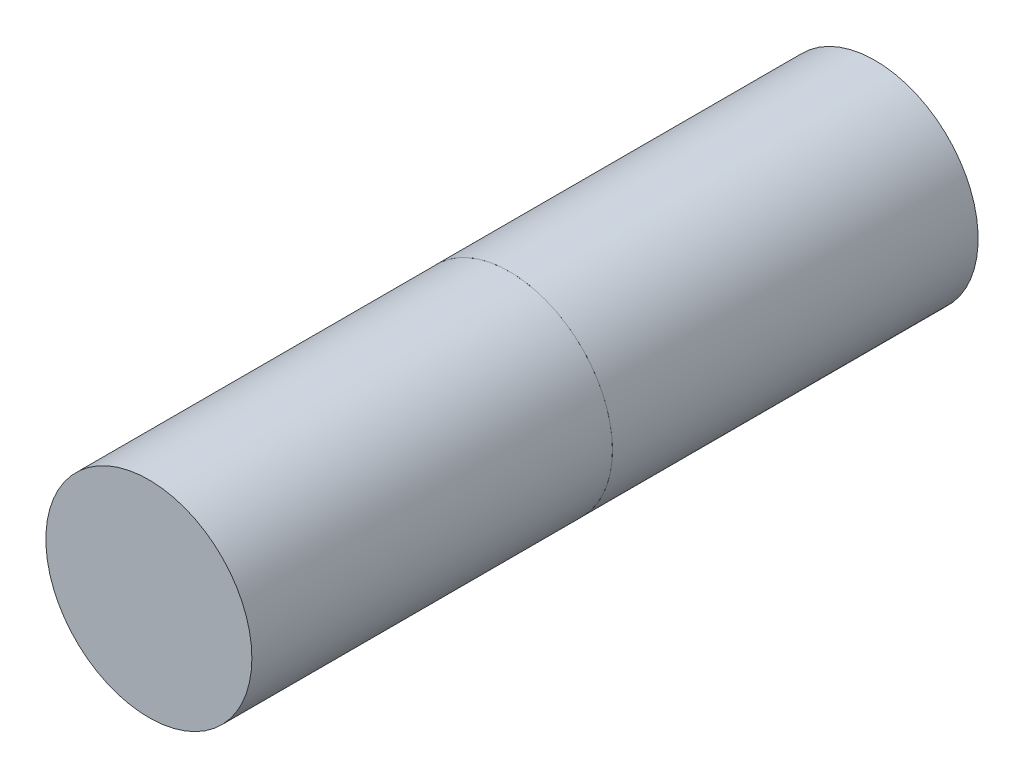
SolidWorks part; units mm, degrees
ref_plane "前视基准面" through (0, 0, 0) normal (0, 0, 1) x (1, 0, 0)
ref_plane "上视基准面" through (0, 0, 0) normal (0, 1, 0) x (1, 0, 0)
ref_plane "右视基准面" through (0, 0, 0) normal (1, 0, 0) x (0, 0, -1)
other "Configuration Table"
sketch "草图1" plane through (0, 0, 0) normal (0, 0, 1) x (1, 0, 0)
  circle A0 centre (0, 0) radius 2
  dimension "D1" = 4
extrude "凸台-拉伸1" add sketch "草图1" along normal blind 7
sketch "草图2" plane through (0, 0, 0) normal (0, 0, -1) x (-1, 0, 0)
  circle A1 centre (0, 0) radius 2
  circle A2 centre (0, 0) radius 2
  dimension "D1" = 0
extrude "凸台-拉伸2" add sketch "草图2" along normal blind 7.1 separate body
